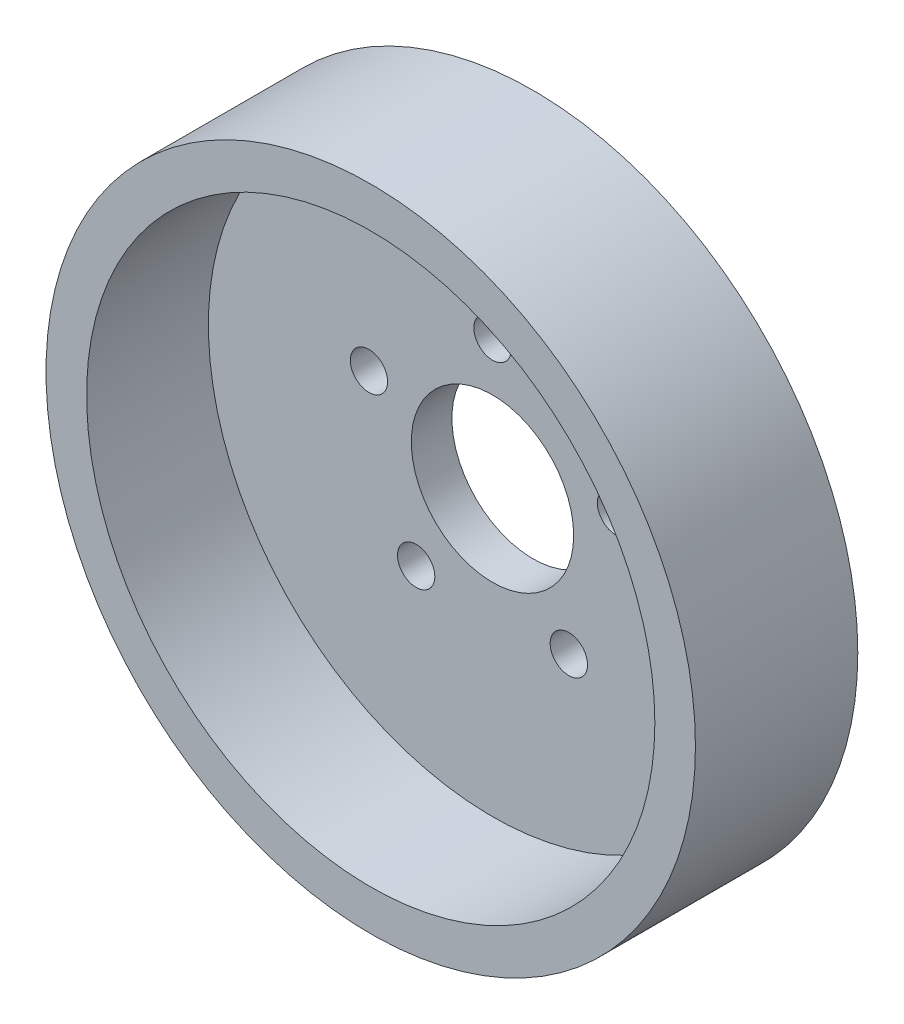
SolidWorks part; units mm, degrees
ref_plane "Front Plane" through (0, 0, 0) normal (0, 0, 1) x (1, 0, 0)
ref_plane "Top Plane" through (0, 0, 0) normal (0, 1, 0) x (1, 0, 0)
ref_plane "Right Plane" through (0, 0, 0) normal (1, 0, 0) x (0, 0, -1)
sketch "Sketch1" plane through (0, 0, 0) normal (0, 0, 1) x (1, 0, 0)
  line L0 (0, 0) -> (0, 20.32) construction
  line L1 (0, 0) -> (19.3255, 6.2792) construction
  line L2 (0, 0) -> (11.9438, -16.4392) construction
  line L3 (0, 0) -> (-11.9438, -16.4392) construction
  line L4 (0, 0) -> (-19.3255, 6.2792) construction
  circle A0 centre (0, 0) radius 50.8
  circle A1 centre (0, 0) radius 12.7
  circle A2 centre (0, 20.32) radius 2.921
  circle A3 centre (19.3255, 6.2792) radius 2.921
  circle A4 centre (11.9438, -16.4392) radius 2.921
  circle A5 centre (-11.9438, -16.4392) radius 2.921
  circle A6 centre (-19.3255, 6.2792) radius 2.921
  point P17 (0, 0)
  dimension "D1" = 25.4
  dimension "D2" = 101.6
  dimension "D3" = 5.842
  dimension "D5" = 20.32
  dimension "D4" = 5
extrude "Boss-Extrude2" add sketch "Sketch1" along normal blind 25.4
sketch "Sketch2" plane through (0, 0, 25.4) normal (0, 0, 1) x (1, 0, 0)
  circle A0 centre (0, 0) radius 44.45
  dimension "D1" = 88.9
extrude "Cut-Extrude1" cut sketch "Sketch2" against normal blind 19.05
